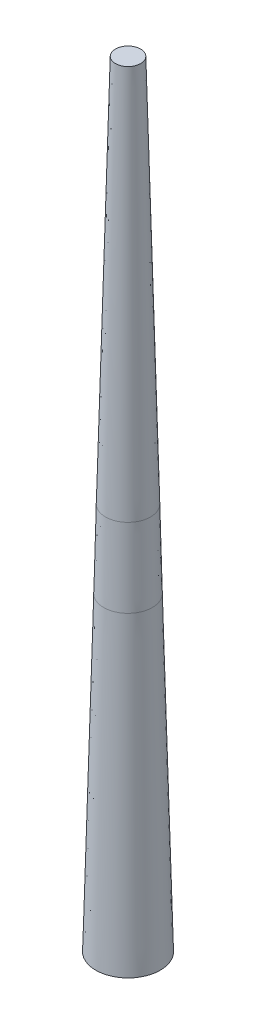
SolidWorks part; units mm, degrees
ref_plane "Alzado" through (0, 0, 0) normal (0, 0, 1) x (1, 0, 0)
ref_plane "Planta" through (0, 0, 0) normal (0, 1, 0) x (1, 0, 0)
ref_plane "Vista lateral" through (0, 0, 0) normal (1, 0, 0) x (0, 0, -1)
sketch "Croquis1" plane through (0, 0, 0) normal (1, 0, 0) x (0, 0, -1)
  line L0 (0, 0) -> (3.25, 0)
  line L1 (3.25, 0) -> (5.8, -100)
  line L2 (5.8, -100) -> (6.26, -120)
  line L3 (6.26, -120) -> (8.3, -200)
  line L4 (8.3, -200) -> (0, -200)
  line L5 (0, -200) -> (0, 0)
  line L6 (5.8, -100) -> (0, -100) construction
  line L7 (6.26, -120) -> (0, -120) construction
  point P7 (0, 0)
  point P10 (49.8689, -86.2438)
  point P11 (0, 0)
  dimension "D1" = 3.25
  dimension "D2" = 200
  dimension "D3" = 100
  dimension "D4" = 5.8
  dimension "D5" = 8.3
  dimension "D6" = 120
revolve "Revolución1" add sketch "Croquis1" angle 360 about L5
